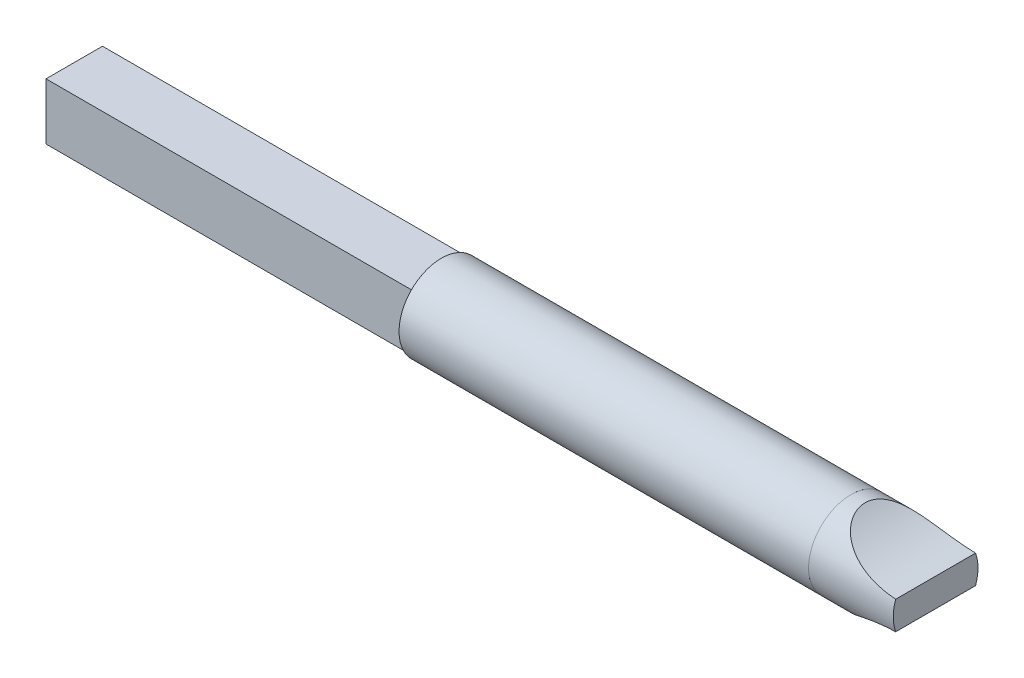
SolidWorks part; units mm, degrees
material "AISI 1020"
ref_plane "Front Plane" through (0, 0, 0) normal (0, 0, 1) x (1, 0, 0)
ref_plane "Top Plane" through (0, 0, 0) normal (0, 1, 0) x (1, 0, 0)
ref_plane "Right Plane" through (0, 0, 0) normal (1, 0, 0) x (0, 0, -1)
sketch "Sketch1" plane through (0, 0, 0) normal (1, 0, 0) x (0, 0, -1)
  line L1 (-1, -1) -> (1, -1)
  line L2 (-1, -1) -> (-1, 1)
  line L3 (-1, 1) -> (1, 1)
  line L4 (1, -1) -> (1, 1)
  line L5 (-1, -1) -> (1, 1) construction
  line L6 (-1, 1) -> (1, -1) construction
  point P0 (0, 0)
  dimension "D1" = 2
  dimension "D2" = 2
ref_plane "Plane1" through (70, 0, 0) normal (1, 0, 0) x (0, 0, -1)
sketch "Sketch12" plane through (70, 0, 0) normal (1, 0, 0) x (0, 0, -1)
  line L0 (-0.0526, 0.2) -> (0.0474, 0.2)
  line L1 (0.0474, 0.2) -> (0.0474, 0.0632)
  line L2 (0.0474, 0.0632) -> (0.2, 0.0632)
  line L3 (0.2, 0.0632) -> (0.2, -0.0368)
  line L4 (0.2, -0.0368) -> (0.0526, -0.0368)
  line L5 (0.0526, -0.0368) -> (0.0526, -0.2)
  line L6 (0.0526, -0.2) -> (-0.0474, -0.2)
  line L7 (-0.0474, -0.2) -> (-0.0474, -0.0368)
  line L8 (-0.0474, -0.0368) -> (-0.2, -0.0368)
  line L9 (-0.2, -0.0368) -> (-0.2, 0.0632)
  line L10 (-0.2, 0.0632) -> (-0.0526, 0.0632)
  line L11 (-0.0526, 0.0632) -> (-0.0526, 0.2)
  line L12 (0, 0) -> (50000, 0) construction
  line L13 (0, -1000) -> (0, 49000) construction
  dimension "D1" = 0.1
  dimension "D2" = 0.1
  dimension "D3" = 0.1
  dimension "D4" = 0.1
  dimension "D5" = 0.2
  dimension "D6" = 0.4
  dimension "D7" = 0.2
  dimension "D8" = 0.2
  dimension "D9" = 0.2
ref_plane "Plane2" through (30, 0, 0) normal (1, 0, 0) x (0, 0, -1)
sketch "Sketch2" plane through (30, 0, 0) normal (1, 0, 0) x (0, 0, -1)
  line L1 (-1, -1) -> (1, -1)
  line L2 (-1, -1) -> (-1, 1)
  line L3 (-1, 1) -> (1, 1)
  line L4 (1, -1) -> (1, 1)
  line L5 (-1, -1) -> (1, 1) construction
  line L6 (-1, 1) -> (1, -1) construction
  point P0 (0, 0)
loft "Loft1" add profiles "Sketch1", "Sketch2"
sketch "Sketch3" plane through (30, 0, 0) normal (1, 0, 0) x (0, 0, -1)
  circle A0 centre (0, 0) radius 3
  dimension "D1" = 6
ref_plane "Plane3" through (64, 0, 0) normal (1, 0, 0) x (0, 0, -1)
sketch "Sketch4" plane through (64, 0, 0) normal (1, 0, 0) x (0, 0, -1)
  circle A0 centre (0, 0) radius 2
extrude "Boss-Extrude1" add sketch "Sketch3" along normal blind 29 contours A0
sketch "Sketch6" plane through (70, 0, 0) normal (1, 0, 0) x (0, 0, -1)
  line L0 (-0.5, 0.5) -> (-0.5, 2)
  line L1 (-0.5, 2) -> (0.5, 2)
  line L2 (0.5, 2) -> (0.5, 0.5)
  line L3 (0.5, 0.5) -> (2, 0.5)
  line L4 (2, 0.5) -> (2, -0.5)
  line L5 (2, -0.5) -> (0.5, -0.5)
  line L6 (0.5, -0.5) -> (0.5, -2)
  line L7 (0.5, -2) -> (-0.5, -2)
  line L8 (-0.5, -2) -> (-0.5, -0.5)
  line L9 (-0.5, -0.5) -> (-2, -0.5)
  line L10 (-2, -0.5) -> (-2, 0.5)
  line L11 (-2, 0.5) -> (-0.5, 0.5)
  line L12 (-7.5281, 0) -> (7.5281, 0) construction
  line L13 (0, 4.9607) -> (0, -4.9607) construction
  point P16 (0, 0)
  point P20 (0, 0)
  dimension "D1" = 1
  dimension "D2" = 1
  dimension "D3" = 1
  dimension "D4" = 1
  dimension "D5" = 0.5
  dimension "D6" = 0.5
  dimension "D7" = 0.5
  dimension "D8" = 0.5
  dimension "D9" = 2
  dimension "D10" = 4
  dimension "D11" = 4
  dimension "D12" = 2
ref_plane "Plane4" through (67, 0, 0) normal (1, 0, 0) x (0, 0, -1)
sketch "Sketch7" plane through (67, 0, 0) normal (1, 0, 0) x (0, 0, -1)
  line L0 (-0.5, 0.5258) -> (-0.5, 1.9992)
  line L1 (-0.5, 1.9992) -> (0.5, 1.9992)
  line L2 (0.5, 1.9992) -> (0.5, 0.5)
  line L3 (0.5, 0.5) -> (2, 0.5)
  line L4 (2, 0.5) -> (2, -0.5)
  line L5 (2, -0.5) -> (0.5798, -0.5)
  line L6 (0.5798, -0.5) -> (0.5798, -2)
  line L7 (0.5798, -2) -> (-0.4202, -2)
  line L8 (-0.4202, -2) -> (-0.4202, -0.4742)
  line L9 (-0.4202, -0.4742) -> (-2, -0.4742)
  line L10 (-2, -0.4742) -> (-2, 0.5258)
  line L11 (-2, 0.5258) -> (-0.5, 0.5258)
  line L12 (-3.5898, 0) -> (3.5898, 0) construction
  line L14 (0, -4.095) -> (0, 4.095) construction
  line L15 (0, 1.9957) -> (0, -1.9957) construction
  point P14 (0.1945, 0.0315)
  point P16 (0, 0)
  point P17 (0.1945, 0.0315)
  point P24 (0, 0)
  point P28 (0, 0)
  dimension "D1" = 0.5
  dimension "D2" = 0.5
  dimension "D3" = 0.5
  dimension "D4" = 0.5
  dimension "D5" = 4
  dimension "D6" = 4
  dimension "D7" = 2
  dimension "D8" = 2
  dimension "D9" = 2
  dimension "D10" = 1.9992
sketch "Sketch14" plane through (59, 0, 0) normal (1, 0, 0) x (0, 0, -1)
  circle A1 centre (0, 0) radius 3
  circle A2 centre (0, 0) radius 3
  dimension "D1" = 0
extrude "Boss-Extrude2" add sketch "Sketch14" along normal blind 6 separate body
sketch "Sketch15" plane through (0, 0, 0) normal (0, 0, 1) x (1, 0, 0)
  line L0 (65, 0) -> (61.3955, 0) construction
  line L1 (65, -3) -> (65, 3) construction
  line L2 (59, 0) -> (30, 0) construction
  line L3 (65, 0) -> (59, 0) construction
  line L4 (65, 3) -> (59, 3) construction
  arc A0 (60, 3) -> (65, 1) centre (65.2978, 8.9945) ccw
  dimension "D3" = 8
  dimension "D1" = 5
  dimension "D2" = 1
extrude "Cut-Extrude1" cut sketch "Sketch15" against normal through all both and the other way through all
mirror "Mirror1" about plane through (0, 0, 0) normal (0, 1, 0) of "Cut-Extrude1"
sketch "Sketch16" plane through (0, 0, 0) normal (-1, 0, 0) x (0, 0, 1)
  line L1 (-2, 2) -> (2, 2)
  line L2 (-2, 2) -> (-2, -2)
  line L3 (-2, -2) -> (2, -2)
  line L4 (2, 2) -> (2, -2)
  line L5 (-2, 2) -> (2, -2) construction
  line L6 (-2, -2) -> (2, 2) construction
  point P0 (0, 0)
  dimension "D1" = 4
  dimension "D2" = 4
extrude "Boss-Extrude3" add sketch "Sketch16" against normal blind 30
sketch "Sketch17" plane through (0, 0, 0) normal (-1, 0, 0) x (0, 0, 1)
  point P0 (0, 0)
sketch "Sketch18" plane through (0, 0, 0) normal (-1, 0, 0) x (0, 0, 1)
  point P0 (0, 0)
sketch "Sketch19" plane through (0, 0, 0) normal (-1, 0, 0) x (0, 0, 1)
  line L1 (-2, -2) -> (2, -2)
  line L2 (-2, -2) -> (-2, 2)
  line L3 (-2, 2) -> (2, 2)
  line L4 (2, -2) -> (2, 2)
  line L5 (-2, -2) -> (2, 2) construction
  line L6 (-2, 2) -> (2, -2) construction
  point P0 (0, 0)
extrude "Cut-Extrude2" cut sketch "Sketch19" against normal blind 4
sketch "Sketch20" plane through (4, 0, 0) normal (-1, 0, 0) x (0, 0, 1)
  line L1 (-2, -2) -> (2, -2)
  line L2 (-2, -2) -> (-2, 2)
  line L3 (-2, 2) -> (2, 2)
  line L4 (2, -2) -> (2, 2)
  line L5 (-2, -2) -> (2, 2) construction
  line L6 (-2, 2) -> (2, -2) construction
  point P0 (0, 0)
sketch "Sketch23" plane through (0, 0, 2) normal (0, 0, 1) x (1, 0, 0)
  line L4 (4, 2) -> (4, -2)
  line L5 (4, -2) -> (30, -2)
  line L6 (30, -2) -> (30, 2)
  line L7 (30, 2) -> (4, 2)
  line L9 (4, -2) -> (30, -2)
  line L10 (30, -2) -> (30, 2)
  line L11 (30, 2) -> (4, 2)
  line L12 (4, 2) -> (4, -2)
  dimension "D1" = 0
sketch "Sketch24" plane through (0, 0, 2) normal (0, 0, 1) x (1, 0, 0)
  line L4 (4, 2) -> (4, -2)
  line L5 (4, -2) -> (30, -2)
  line L6 (30, -2) -> (30, 2)
  line L7 (30, 2) -> (4, 2)
  line L8 (4, 2) -> (4, -2)
  line L9 (4, -2) -> (30, -2)
  line L10 (30, -2) -> (30, 2)
  line L11 (30, 2) -> (4, 2)
  dimension "D1" = 0
sketch "Sketch25" plane through (4, 0, 0) normal (-1, 0, 0) x (0, 0, 1)
  point P0 (0, 0)
sketch "Sketch26" plane through (0, 0, 0) normal (0, 0, 1) x (1, 0, 0)
  line L0 (65, -1) -> (65, 1) construction
  line L1 (65, -1) -> (65, 1)
